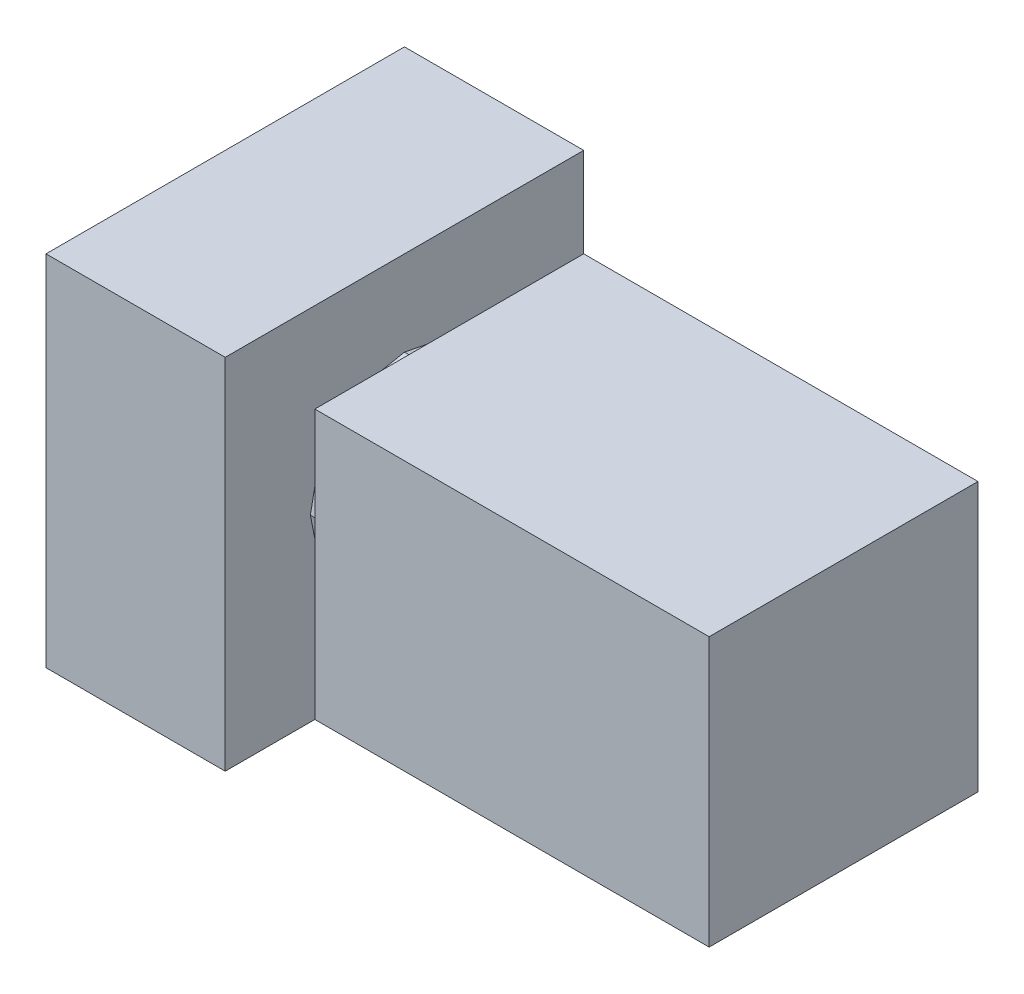
SolidWorks part; units mm, degrees
ref_plane "Front Plane" through (0, 0, 0) normal (0, 0, 1) x (1, 0, 0)
ref_plane "Top Plane" through (0, 0, 0) normal (0, 1, 0) x (1, 0, 0)
ref_plane "Right Plane" through (0, 0, 0) normal (1, 0, 0) x (0, 0, -1)
ref_plane "PL_Head_base" through (0, 0, 215) normal (0, 0, 1) x (1, 0, 0)
sketch "SK_Head" plane through (0, 0, 215) normal (0, 0, 1) x (1, 0, 0)
  line L0 (-94, -20) -> (-74, -20)
  line L1 (-74, -20) -> (-74, 20)
  line L2 (-74, 20) -> (-94, 20)
  line L3 (-94, 20) -> (-94, -20)
  dimension "P1" = 94
  dimension "P2" = 20
  dimension "P3" = 74
  dimension "P4" = 20
  dimension "P5" = 74
  dimension "P6" = 20
  dimension "P7" = 94
  dimension "P8" = 20
extrude "Head" add sketch "SK_Head" along normal blind 40
ref_plane "PL_Bushing_base" through (-74.5, 0, 0) normal (1, 0, 0) x (0, 0, -1)
sketch "SK_Bushing" plane through (-74.5, 0, 0) normal (1, 0, 0) x (0, 0, -1)
  line L0 (-239.0182, 9.7007) -> (-242.4246, 7.4246)
  line L1 (-242.4246, 7.4246) -> (-244.7007, 4.0182)
  line L2 (-244.7007, 4.0182) -> (-245.5, 0)
  line L3 (-245.5, 0) -> (-244.7007, -4.0182)
  line L4 (-244.7007, -4.0182) -> (-242.4246, -7.4246)
  line L5 (-242.4246, -7.4246) -> (-239.0182, -9.7007)
  line L6 (-239.0182, -9.7007) -> (-235, -10.5)
  line L7 (-235, -10.5) -> (-230.9818, -9.7007)
  line L8 (-230.9818, -9.7007) -> (-227.5754, -7.4246)
  line L9 (-227.5754, -7.4246) -> (-225.2993, -4.0182)
  line L10 (-225.2993, -4.0182) -> (-224.5, 0)
  line L11 (-224.5, 0) -> (-225.2993, 4.0182)
  line L12 (-225.2993, 4.0182) -> (-227.5754, 7.4246)
  line L13 (-227.5754, 7.4246) -> (-230.9818, 9.7007)
  line L14 (-230.9818, 9.7007) -> (-235, 10.5)
  line L15 (-235, 10.5) -> (-239.0182, 9.7007)
  dimension "P1" = 239.0182
  dimension "P2" = 9.7007
  dimension "P3" = 242.4246
  dimension "P4" = 7.4246
  dimension "P5" = 244.7007
  dimension "P6" = 4.0182
  dimension "P7" = 245.5
  dimension "P8" = 244.7007
  dimension "P9" = 4.0182
  dimension "P10" = 242.4246
  dimension "P11" = 7.4246
  dimension "P12" = 239.0182
  dimension "P13" = 9.7007
  dimension "P14" = 235
  dimension "P15" = 10.5
  dimension "P16" = 230.9818
  dimension "P17" = 9.7007
  dimension "P18" = 227.5754
  dimension "P19" = 7.4246
  dimension "P20" = 225.2993
  dimension "P21" = 4.0182
  dimension "P22" = 224.5
  dimension "P23" = 225.2993
  dimension "P24" = 4.0182
  dimension "P25" = 227.5754
  dimension "P26" = 7.4246
  dimension "P27" = 230.9818
  dimension "P28" = 9.7007
  dimension "P29" = 235
  dimension "P30" = 10.5
extrude "Bushing" add sketch "SK_Bushing" along normal blind 6
ref_plane "PL_Contact_Block_base" through (0, 0, 220) normal (0, 0, 1) x (1, 0, 0)
sketch "SK_Contact_Block" plane through (0, 0, 220) normal (0, 0, 1) x (1, 0, 0)
  line L0 (-69, -15) -> (-25, -15)
  line L1 (-25, -15) -> (-25, 15)
  line L2 (-25, 15) -> (-69, 15)
  line L3 (-69, 15) -> (-69, -15)
  dimension "P1" = 69
  dimension "P2" = 15
  dimension "P3" = 25
  dimension "P4" = 15
  dimension "P5" = 25
  dimension "P6" = 15
  dimension "P7" = 69
  dimension "P8" = 15
extrude "Contact_Block" add sketch "SK_Contact_Block" along normal blind 30
